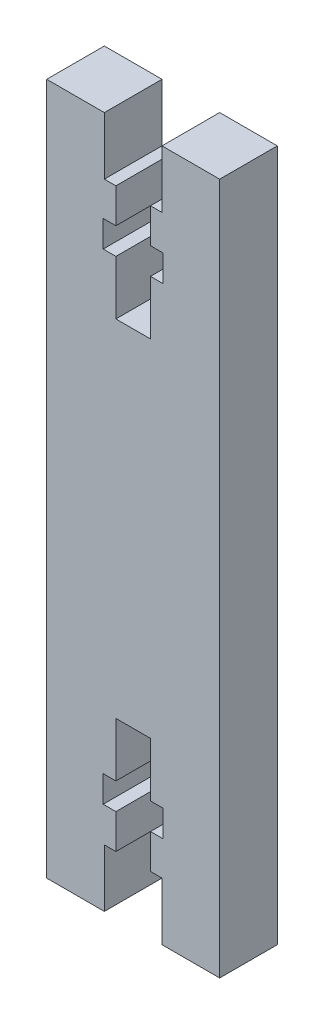
SolidWorks part; units mm, degrees
ref_plane "Plan de face" through (0, 0, 0) normal (0, 0, 1) x (1, 0, 0)
ref_plane "Plan de dessus" through (0, 0, 0) normal (0, 1, 0) x (1, 0, 0)
ref_plane "Plan de droite" through (0, 0, 0) normal (1, 0, 0) x (0, 0, -1)
sketch "Esquisse1" plane through (0, 0, 0) normal (0, 0, 1) x (1, 0, 0)
  line L0 (-7.5, 0) -> (-7.5, 50)
  line L1 (7.5, 0) -> (7.5, 50)
  line L2 (-7.5, 25) -> (7.5, 25) construction
  line B0 (-2.6, 3) -> (-2.6, 5.3)
  line B1 (1.5, 5.3) -> (1.5, 10)
  line B2 (-1.5, 10) -> (-1.5, 5.3)
  line B3 (-2.6, 5.3) -> (-1.5, 5.3)
  line B4 (0, 0) -> (0, 11.2208) construction
  line B5 (-1.5, 0) -> (-2.5, 0)
  line B6 (-2.5, -5) -> (-7.5, -5)
  line B7 (-7.5, -5) -> (-7.5, 0)
  line B8 (-2.5, -5) -> (-2.5, 0)
  line B9 (1.5, 0) -> (2.5, 0)
  line B10 (2.5, 0) -> (2.5, -5)
  line B11 (2.5, -5) -> (7.5, -5)
  line B12 (7.5, -5) -> (7.5, 0)
  line B13 (1.5, 0) -> (1.5, 3)
  line B14 (-1.5, 0) -> (1.5, 0) construction
  line B15 (1.5, 5.3) -> (2.6, 5.3)
  line B16 (2.6, 3) -> (1.5, 3)
  line B17 (1.5, 10) -> (-1.5, 10)
  line B18 (-1.5, 3) -> (-2.6, 3)
  line B19 (2.6, 5.3) -> (2.6, 3)
  line B20 (-1.5, 3) -> (-1.5, 0)
  line B21 (0, 10) -> (0, 0) construction
  line B22 (-2.6, 47) -> (-2.6, 44.7)
  line B23 (1.5, 44.7) -> (1.5, 40)
  line B24 (-1.5, 40) -> (-1.5, 44.7)
  line B25 (-2.6, 44.7) -> (-1.5, 44.7)
  line B26 (0, 50) -> (0, 38.7792) construction
  line B27 (-1.5, 50) -> (-2.5, 50)
  line B28 (-2.5, 55) -> (-7.5, 55)
  line B29 (-7.5, 55) -> (-7.5, 50)
  line B30 (-2.5, 55) -> (-2.5, 50)
  line B31 (1.5, 50) -> (2.5, 50)
  line B32 (2.5, 50) -> (2.5, 55)
  line B33 (2.5, 55) -> (7.5, 55)
  line B34 (7.5, 55) -> (7.5, 50)
  line B35 (1.5, 50) -> (1.5, 47)
  line B36 (-1.5, 50) -> (1.5, 50) construction
  line B37 (1.5, 44.7) -> (2.6, 44.7)
  line B38 (2.6, 47) -> (1.5, 47)
  line B39 (1.5, 40) -> (-1.5, 40)
  line B40 (-1.5, 47) -> (-2.6, 47)
  line B41 (2.6, 44.7) -> (2.6, 47)
  line B42 (-1.5, 47) -> (-1.5, 50)
  line B43 (0, 40) -> (0, 50) construction
  dimension "D1" = 50
sketch_block_instance "Insert M3 plots ep 5mm-1"
sketch_block "Insert M3 plots ep 5mm" parameters "D1"=5, "D2"=5, "D3"=5
sketch_block_instance "Decoupe Insert M3-4"
sketch_block "Decoupe Insert M3" parameters "D1"=5.2, "D2"=3, "D3"=2.3, "D4"=3, "D5"=10
sketch_block_instance "Insert M3 plots ep 5mm-3"
extrude "Boss.-Extru.1" add sketch "Esquisse1" along normal blind 5 contours L0 L2 L1 B34 B33 B32 B31 B35 B38 B41 B37 B23 B39 B24 B25 B22 B40 B42 B27 B30 B28 B29 | L2 L0 B7 B6 B8 B5 B20 B18 B0 B3 B2 B17 B1 B15 B19 B16 B13 B9 B10 B11 B12 L1
